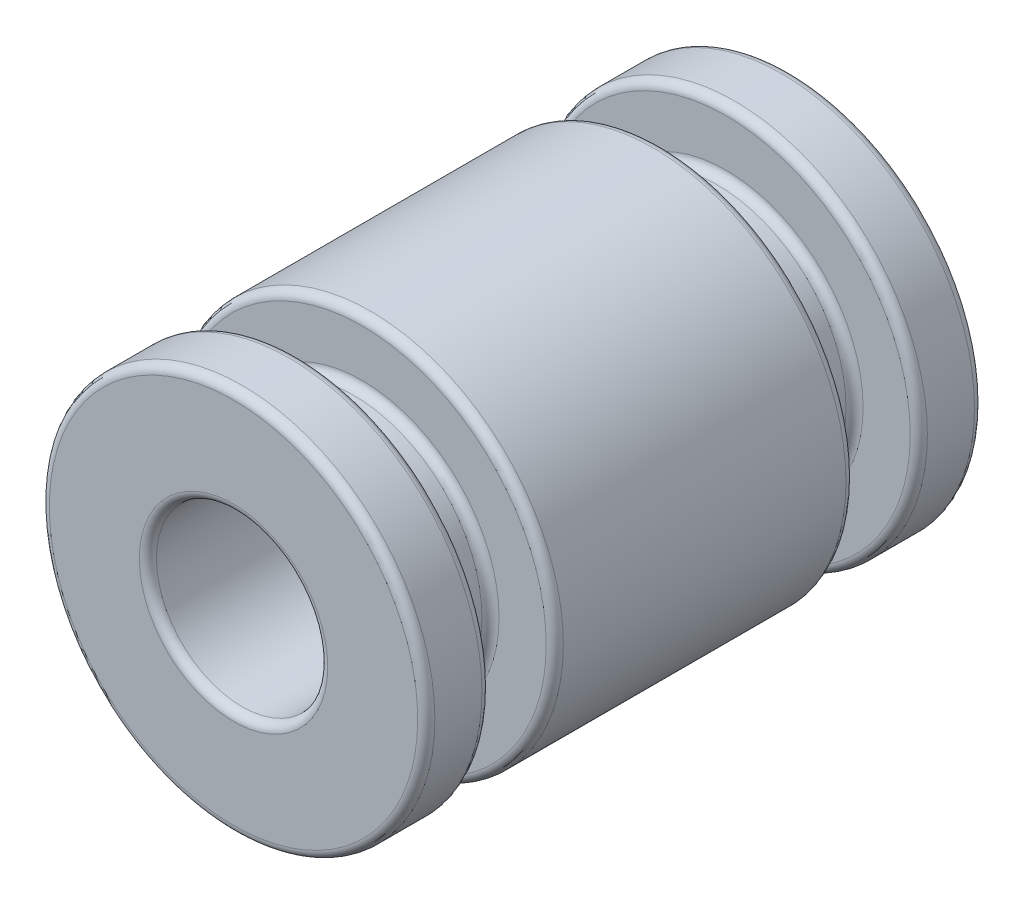
SolidWorks part; units mm, degrees
ref_plane "Front Plane" through (0, 0, 0) normal (0, 0, 1) x (1, 0, 0)
ref_plane "Top Plane" through (0, 0, 0) normal (0, 1, 0) x (1, 0, 0)
ref_plane "Right Plane" through (0, 0, 0) normal (1, 0, 0) x (0, 0, -1)
sketch "Sketch1" plane through (0, 0, 0) normal (0, 1, 0) x (1, 0, 0)
  line L0 (2, 6.3) -> (2, -6.3)
  line L1 (2.2, -6.5) -> (4.3, -6.5)
  line L2 (4.5, -6.3) -> (4.5, -5.2)
  line L3 (4.3, -5) -> (3.2, -5)
  line L4 (3, -4.8) -> (3, -3.7)
  line L5 (3.2, -3.5) -> (4.3, -3.5)
  line L6 (4.5, -3.3) -> (4.5, 3.3)
  line L7 (4.3, 3.5) -> (3.2, 3.5)
  line L8 (3, 3.7) -> (3, 4.8)
  line L9 (3.2, 5) -> (4.3, 5)
  line L10 (4.5, 5.2) -> (4.5, 6.3)
  line L11 (4.3, 6.5) -> (2.2, 6.5)
  line L12 (0, 6.503) -> (0, -6.503) construction
  arc A0 (2.2, 6.5) -> (2, 6.3) centre (2.2, 6.3) ccw
  arc A1 (2, -6.3) -> (2.2, -6.5) centre (2.2, -6.3) ccw
  arc A2 (4.3, -6.5) -> (4.5, -6.3) centre (4.3, -6.3) ccw
  arc A3 (4.5, -5.2) -> (4.3, -5) centre (4.3, -5.2) ccw
  arc A4 (3.2, -5) -> (3, -4.8) centre (3.2, -4.8) cw
  arc A5 (3, -3.7) -> (3.2, -3.5) centre (3.2, -3.7) cw
  arc A6 (4.3, -3.5) -> (4.5, -3.3) centre (4.3, -3.3) ccw
  arc A7 (4.5, 3.3) -> (4.3, 3.5) centre (4.3, 3.3) ccw
  arc A8 (3.2, 3.5) -> (3, 3.7) centre (3.2, 3.7) cw
  arc A9 (3, 4.8) -> (3.2, 5) centre (3.2, 4.8) cw
  arc A10 (4.3, 5) -> (4.5, 5.2) centre (4.3, 5.2) ccw
  arc A11 (4.5, 6.3) -> (4.3, 6.5) centre (4.3, 6.3) ccw
revolve "Revolve1" add sketch "Sketch1" angle 360 about L12
